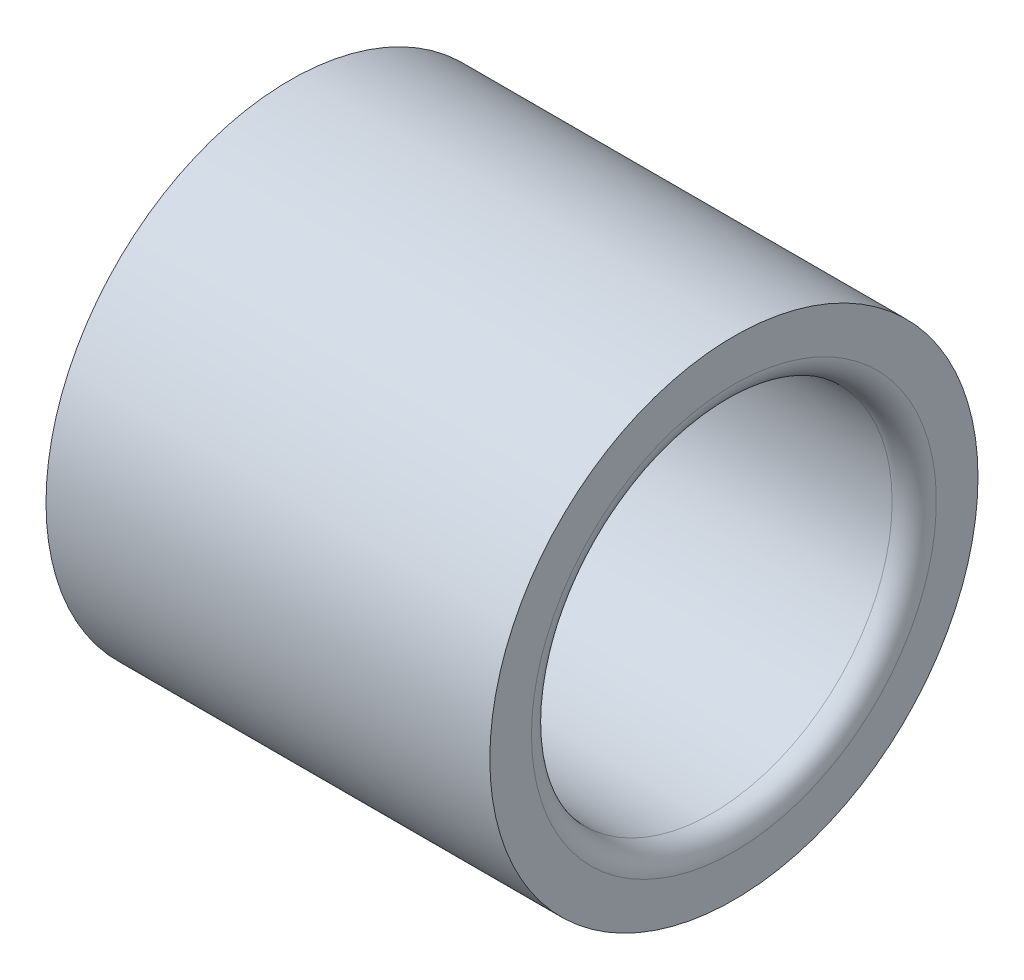
SolidWorks part; units mm, degrees
ref_plane "Front Plane" through (0, 0, 0) normal (0, 0, 1) x (1, 0, 0)
ref_plane "Top Plane" through (0, 0, 0) normal (0, 1, 0) x (1, 0, 0)
ref_plane "Right Plane" through (0, 0, 0) normal (1, 0, 0) x (0, 0, -1)
sketch "Sketch1" plane through (0, 0, 0) normal (0, 0, 1) x (1, 0, 0)
  line L0 (0, 0) -> (5, 0)
  line L1 (5, 0) -> (5, 4)
  line L2 (5, 4) -> (20, 4)
  line L3 (20, 4) -> (20, 7)
  line L4 (20, 7) -> (0, 7)
  line L5 (0, 7) -> (0, 0)
  line L6 (-15.2208, -4) -> (25.9221, -4) construction
  dimension "D1" = 4
  dimension "D2" = 4
  dimension "D3" = 5
  dimension "D4" = 20
  dimension "D5" = 3
revolve "Revolve1" add sketch "Sketch1" angle 360 about L6
draft "Draft1" type of draft neutral plane draft angle 0.5 faces to draft 1 face at (20, -4, 8) neutral plane through (5, 0, 0) neutral plane normal (1, 0, 0) parameters "D1"=0.5
fillet "Fillet2" radius 1 1 edges at (20, -4, 8.1309)
